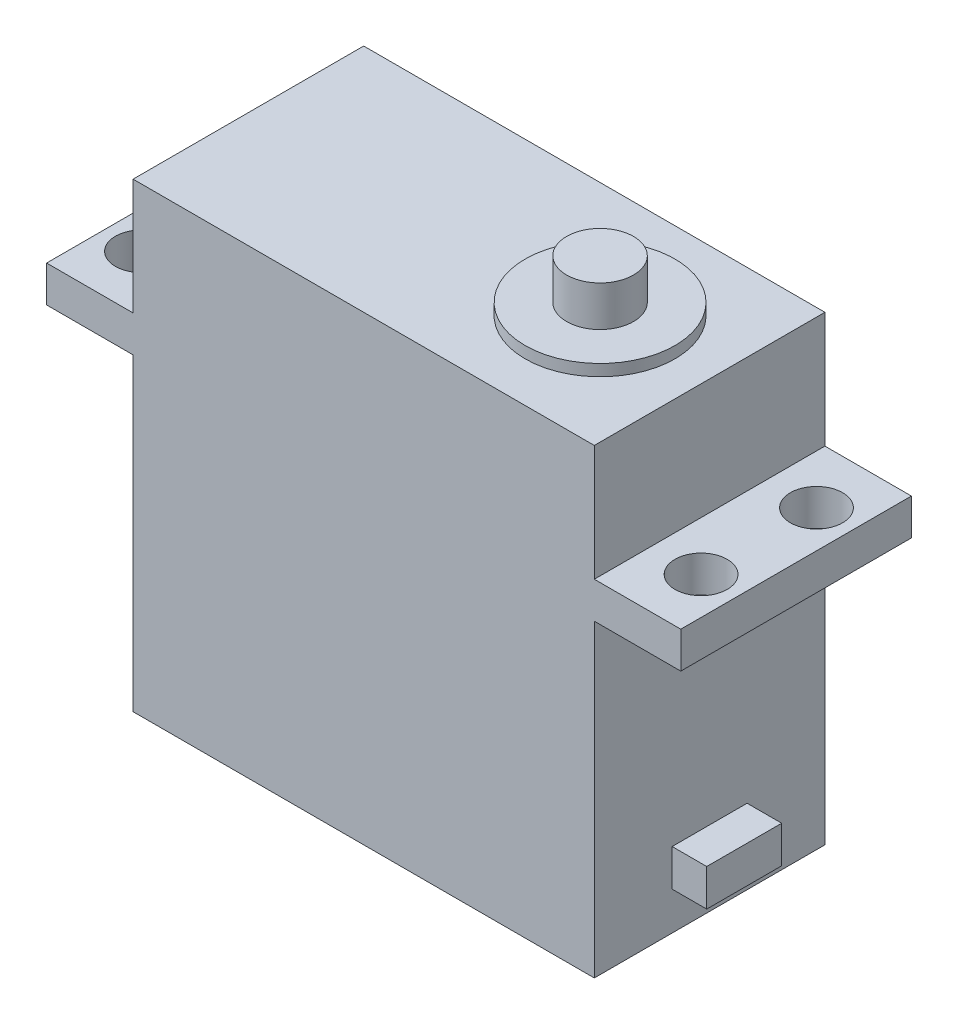
SolidWorks part; units mm, degrees
ref_plane "Front" through (0, 0, 0) normal (0, 0, 1) x (1, 0, 0)
ref_plane "Top" through (0, 0, 0) normal (0, 1, 0) x (1, 0, 0)
ref_plane "Right" through (0, 0, 0) normal (1, 0, 0) x (0, 0, -1)
sketch "Sketch1" plane through (0, 0, 0) normal (0, 1, 0) x (1, 0, 0)
  line L1 (-20, 10) -> (20, 10)
  line L2 (-20, 10) -> (-20, -10)
  line L3 (-20, -10) -> (20, -10)
  line L4 (20, 10) -> (20, -10)
  line L5 (-20, 10) -> (20, -10) construction
  line L6 (-20, -10) -> (20, 10) construction
  point P0 (0, 0)
  dimension "D1" = 40
  dimension "D2" = 20
extrude "Boss-Extrude1" add sketch "Sketch1" along normal blind 40
sketch "Sketch2" plane through (0, 40, 0) normal (0, 1, 0) x (1, 0, 0)
  line L0 (20, 10) -> (-20, 10) construction
  line L1 (-27.5, 10) -> (27.5, 10)
  line L2 (-27.5, 10) -> (-27.5, -10)
  line L3 (-27.5, -10) -> (27.5, -10)
  line L4 (27.5, 10) -> (27.5, -10)
  line L5 (-27.5, 10) -> (27.5, -10) construction
  line L6 (-27.5, -10) -> (27.5, 10) construction
  point P0 (0, 0)
  dimension "D1" = 55
extrude "Boss-Extrude2" add sketch "Sketch2" along normal blind 3.15 from offset 13.2 offset against normal yes
sketch "Sketch4" plane through (0, 29.95, 0) normal (0, 1, 0) x (1, 0, 0)
  line L0 (-20, 10) -> (-27.5, 10) construction
  line L1 (-22, 0) -> (22, 0) construction
  line L2 (-24.265, 0) -> (24.265, 0) construction
  line L3 (0, -11) -> (0, 11) construction
  circle A0 centre (-24.265, 5.005) radius 2.265
  circle A1 centre (-24.265, -5.005) radius 2.265
  circle A4 centre (24.265, -5.005) radius 2.265
  circle A5 centre (24.265, 5.005) radius 2.265
  point P15 (0, 0)
  dimension "D1" = 4.53
  dimension "D2" = 4.995
  dimension "D3" = 48.53
extrude "Cut-Extrude1" cut sketch "Sketch4" against normal through all both and the other way through all
sketch "Sketch5" plane through (0, 40, 0) normal (0, 1, 0) x (1, 0, 0)
  line L0 (-22, 0) -> (22, 0) construction
  line L1 (20, -10) -> (20, 10) construction
  circle A0 centre (10.5, 0) radius 6.5
  dimension "D1" = 13
  dimension "D2" = 9.5
extrude "Boss-Extrude3" add sketch "Sketch5" along normal blind 1
sketch "Sketch7" plane through (0, 41, 0) normal (0, 1, 0) x (1, 0, 0)
  circle A0 centre (10.5, 0) radius 2.9
  dimension "D1" = 5.8
extrude "Boss-Extrude4" add sketch "Sketch7" along normal blind 3.5
sketch "Sketch8" plane through (20, 0, 0) normal (1, 0, 0) x (0, 0, -1)
  line L0 (0, 24.475) -> (0, -24.475) construction
  line L1 (-3.25, 6.5) -> (3.25, 6.5)
  line L2 (-3.25, 6.5) -> (-3.25, 3.3)
  line L3 (-3.25, 3.3) -> (3.25, 3.3)
  line L4 (3.25, 6.5) -> (3.25, 3.3)
  line L5 (-3.25, 6.5) -> (3.25, 3.3) construction
  line L6 (-3.25, 3.3) -> (3.25, 6.5) construction
  line L7 (11, 0) -> (-11, 0) construction
  point P0 (0, 4.9)
  dimension "D1" = 3.2
  dimension "D2" = 3.3
  dimension "D3" = 6.5
extrude "Boss-Extrude5" add sketch "Sketch8" along normal blind 3
